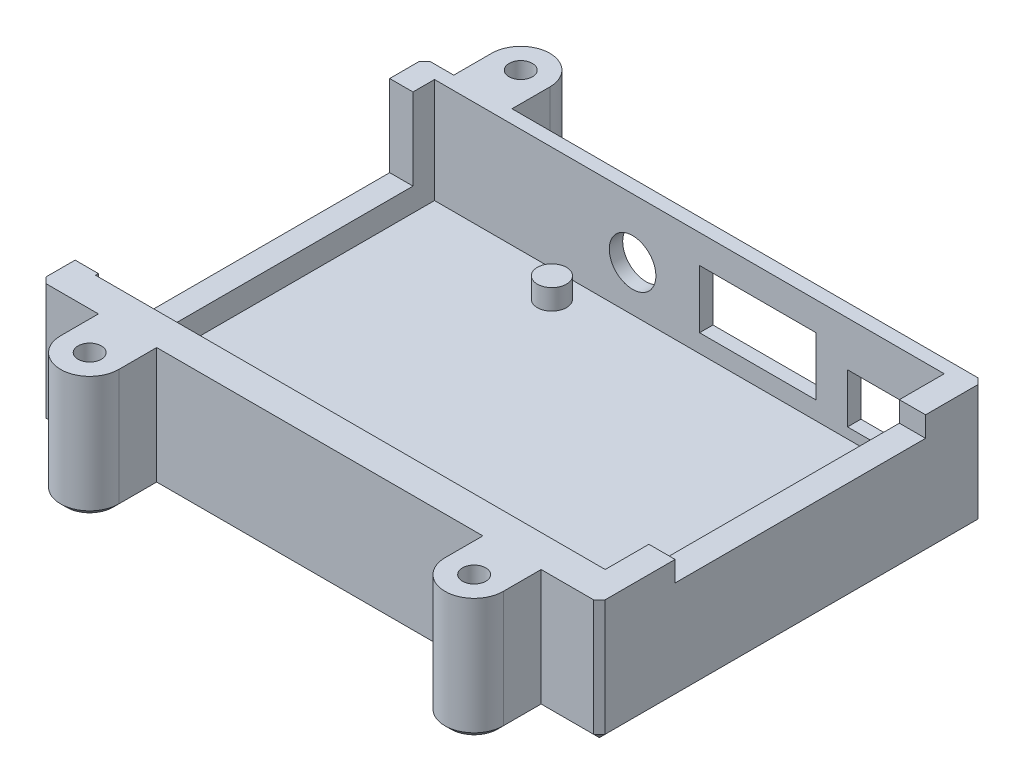
SolidWorks part; units mm, degrees
ref_plane "Front Plane" through (0, 0, 0) normal (0, 0, 1) x (1, 0, 0)
ref_plane "Top Plane" through (0, 0, 0) normal (0, 1, 0) x (1, 0, 0)
ref_plane "Right Plane" through (0, 0, 0) normal (1, 0, 0) x (0, 0, -1)
sketch "Sketch1" plane through (0, 0, 0) normal (0, 1, 0) x (1, 0, 0)
  line L0 (-33, -33) -> (-33, -39.5) construction
  line L1 (48, 33) -> (-48, 33)
  line L2 (48, 33) -> (48, -33)
  line L3 (48, -33) -> (-48, -33)
  line L4 (-48, 33) -> (-48, -33)
  line L5 (48, 33) -> (-48, -33) construction
  line L6 (48, -33) -> (-48, 33) construction
  line L7 (-28, -33) -> (-28, -39.5)
  line L8 (-38, -33) -> (-38, -39.5)
  line L9 (0, 18.5223) -> (0, -49.7489) construction
  line L10 (33, -33) -> (33, -39.5) construction
  line L11 (28, -33) -> (28, -39.5)
  line L12 (38, -33) -> (38, -39.5)
  line L13 (-38, 39.5) -> (-38, 33) construction
  line L14 (-33, 39.5) -> (-33, 33)
  line L15 (-43, 39.5) -> (-43, 33)
  arc A0 (-28, -33) -> (-38, -33) centre (-33, -33) ccw
  arc A1 (-38, -39.5) -> (-28, -39.5) centre (-33, -39.5) ccw
  arc A2 (28, -33) -> (38, -33) centre (33, -33) cw
  arc A3 (38, -39.5) -> (28, -39.5) centre (33, -39.5) cw
  arc A4 (-33, 39.5) -> (-43, 39.5) centre (-38, 39.5) ccw
  arc A5 (-43, 33) -> (-33, 33) centre (-38, 33) ccw
  circle A6 centre (-38, 39.5) radius 2
  circle A7 centre (-33, -39.5) radius 2
  circle A8 centre (33, -39.5) radius 2
  point P0 (0, 0)
  point P8 (-33, -36.25)
  point P17 (33, -36.25)
  point P24 (-38, 36.25)
  dimension "D3" = 5
  dimension "D6" = 5
  dimension "D9" = 4
  dimension "D1" = 66
  dimension "D2" = 96
  dimension "D4" = 15
  dimension "D5" = 6.5
  dimension "D7" = 6.5
  dimension "D8" = 10
extrude "Boss-Extrude2" add sketch "Sketch1" along normal blind 3 contours L4 L3 L2 L1
sketch "Sketch4" plane through (0, 0, 0) normal (0, 1, 0) x (1, 0, 0)
  line L0 (-38, 33) -> (-38, 39.5) construction
  line L1 (48, 33) -> (-48, 33) construction
  line L2 (-43, 33) -> (-43, 39.5)
  line L3 (-33, 33) -> (-33, 39.5)
  line L4 (-33, -33) -> (-33, -39.5) construction
  line L5 (48, -33) -> (-48, -33) construction
  line L6 (-28, -33) -> (-28, -39.5)
  line L7 (-38, -33) -> (-38, -39.5)
  line L8 (33, -33) -> (33, -39.5) construction
  line L9 (38, -33) -> (38, -39.5)
  line L10 (28, -33) -> (28, -39.5)
  line L11 (-48, 33) -> (-48, -33) construction
  line L12 (48, 33) -> (48, -33) construction
  arc A0 (-43, 33) -> (-33, 33) centre (-38, 33) ccw
  arc A1 (-33, 39.5) -> (-43, 39.5) centre (-38, 39.5) ccw
  arc A2 (-28, -33) -> (-38, -33) centre (-33, -33) ccw
  arc A3 (-38, -39.5) -> (-28, -39.5) centre (-33, -39.5) ccw
  arc A4 (38, -33) -> (28, -33) centre (33, -33) ccw
  arc A5 (28, -39.5) -> (38, -39.5) centre (33, -39.5) ccw
  circle A6 centre (-38, 39.5) radius 2
  circle A9 centre (-33, -39.5) radius 2
  circle A10 centre (33, -39.5) radius 2
  point P4 (-38, 36.25)
  point P9 (-33, -36.25)
  point P18 (33, -36.25)
  dimension "D2" = 5
  dimension "D4" = 15
  dimension "D6" = 4
  dimension "D1" = 6.5
  dimension "D3" = 10
  dimension "D5" = 15
extrude "Boss-Extrude3" add sketch "Sketch4" along normal blind 3
sketch "Sketch8" plane through (0, 3, 0) normal (0, 1, 0) x (1, 0, 0)
  line L0 (43.5, 30.7) -> (43.5, -27.5)
  line L1 (43.5, 30.7) -> (-44, 30.7)
  line L2 (48, 33) -> (48, -33) construction
  line L3 (48, 33) -> (-33, 33) construction
  line L4 (-44, 30.7) -> (-44, -27.5)
  line L5 (-48, 33) -> (-48, -33) construction
  line L6 (-44, -27.5) -> (43.5, -27.5)
  line L7 (28, -33) -> (-28, -33) construction
  line L8 (-0.25, 30.7) -> (-0.25, -27.5) construction
  line L9 (-44, 1.6) -> (43.5, 1.6) construction
  line L10 (38.75, 26.1) -> (38.75, -22.9) construction
  line L11 (42.25, 29.6) -> (-42.75, 29.6)
  line L12 (42.25, 29.6) -> (42.25, -26.4)
  line L13 (42.25, -26.4) -> (-42.75, -26.4)
  line L14 (-42.75, 29.6) -> (-42.75, -26.4)
  line L15 (42.25, 29.6) -> (-42.75, -26.4) construction
  line L16 (42.25, -26.4) -> (-42.75, 29.6) construction
  line L17 (-19.25, 26.1) -> (38.75, 26.1) construction
  line L18 (-48, 33) -> (-48, -33)
  line L19 (-48, -33) -> (48, -33)
  line L20 (48, -33) -> (48, 33)
  line L21 (48, 33) -> (-48, 33)
  circle A0 centre (38.75, 26.1) radius 2.5
  circle A1 centre (38.75, -22.9) radius 2.5
  circle A2 centre (-19.25, 26.1) radius 2.5
  circle A3 centre (-19.25, -22.9) radius 2.5
  point P16 (-0.25, 1.6)
  point P25 (38.75, 1.6)
  dimension "D7" = 5
  dimension "D8" = 49
  dimension "D10" = 49
  dimension "D1" = 4.5
  dimension "D2" = 2.3
  dimension "D3" = 4
  dimension "D4" = 5.5
  dimension "D5" = 85
  dimension "D6" = 56
  dimension "D9" = 58
  dimension "D11" = 3.5
  dimension "D12" = 3.5
extrude "Boss-Extrude5" add sketch "Sketch8" along normal blind 3.5 contours A2 | A0 | A1 | A3
sketch "Sketch9" plane through (0, 3, 0) normal (0, 1, 0) x (1, 0, 0)
  line L0 (-48, 33) -> (-48, -33) construction
  line L1 (-44, -27.5) -> (43.5, -27.5)
  line L2 (-44, -27.5) -> (-44, 30.7)
  line L3 (-44, 30.7) -> (43.5, 30.7)
  line L4 (43.5, -27.5) -> (43.5, 30.7)
  line L5 (48, 33) -> (-33, 33) construction
  line L6 (48, 33) -> (48, -33) construction
  line L7 (28, -33) -> (-28, -33) construction
  line L9 (-48, -33) -> (48, -33)
  line L10 (-48, -33) -> (-48, 33)
  line L11 (-48, 33) -> (48, 33)
  line L12 (48, -33) -> (48, 33)
  dimension "D1" = 4
  dimension "D2" = 2.3
  dimension "D3" = 4.5
  dimension "D4" = 5.5
extrude "Boss-Extrude6" add sketch "Sketch9" along normal blind 18
sketch "Sketch11" plane through (-48, 0, 0) normal (-1, 0, 0) x (0, 0, 1)
  line L0 (-33, 21) -> (33, 21) construction
  line L1 (-27, 21) -> (27, 21)
  line L2 (-27, 21) -> (-27, 7)
  line L3 (-27, 7) -> (27, 7)
  line L4 (27, 21) -> (27, 7)
  line L5 (-33, 21) -> (-33, 0) construction
  line L6 (33, 21) -> (33, 0) construction
  dimension "D1" = 14
  dimension "D2" = 54
  dimension "D3" = 6
  dimension "D4" = 6
extrude "Cut-Extrude1" cut sketch "Sketch11" against normal up to surface (4 mm away) up to face at (-44, 12, -1.6)
sketch "Sketch12" plane through (48, 0, 0) normal (1, 0, 0) x (0, 0, -1)
  line L0 (-33, 21) -> (33, 21) construction
  line L1 (-20, 21) -> (23, 21)
  line L2 (-20, 21) -> (-20, 17.5)
  line L3 (-20, 17.5) -> (23, 17.5)
  line L4 (23, 21) -> (23, 17.5)
  line L5 (-33, 21) -> (-33, 0) construction
  line L6 (33, 21) -> (33, 0) construction
  dimension "D1" = 3.5
  dimension "D2" = 13
  dimension "D3" = 10
extrude "Cut-Extrude2" cut sketch "Sketch12" against normal up to surface (4.5 mm away) up to face at (43.5, 12, -1.6)
sketch "Sketch13" plane through (43.5, 0, 0) normal (-1, 0, 0) x (0, 0, 1)
  line L0 (27.5, 3) -> (-30.7, 3) construction
  line L1 (-9.075, 3) -> (6.925, 3)
  line L2 (-9.075, 3) -> (-9.075, 8)
  line L3 (-9.075, 8) -> (6.925, 8)
  line L4 (6.925, 3) -> (6.925, 8)
  line L10 (-30.7, 21) -> (-30.7, 3) construction
  point P6 (-1.075, 8)
  dimension "D1" = 16
  dimension "D2" = 29.625
  dimension "D3" = 5
extrude "Cut-Extrude3" cut sketch "Sketch13" against normal blind 3.5
sketch "Sketch14" plane through (0, 0, -33) normal (0, 0, -1) x (-1, 0, 0)
  line L1 (-38.9, 4.8) -> (-26.9, 4.8)
  line L2 (-38.9, 4.8) -> (-38.9, 13.3)
  line L3 (-38.9, 13.3) -> (-26.9, 13.3)
  line L4 (-26.9, 4.8) -> (-26.9, 13.3)
  line L5 (-48, 0) -> (33, 0) construction
  line L6 (-48, 21) -> (-48, 0) construction
  line L7 (-21.5, 6.1) -> (-1.5, 6.1)
  line L8 (-21.5, 6.1) -> (-21.5, 16.1)
  line L9 (-21.5, 16.1) -> (-1.5, 16.1)
  line L10 (-1.5, 6.1) -> (-1.5, 16.1)
  circle A0 centre (10, 10.8) radius 4
  point P4 (-32.9, 13.3)
  point P13 (-11.5, 16.1)
  point P16 (-38.9, 9.05)
  point P17 (-21.5, 11.1)
  dimension "D9" = 8
  dimension "D1" = 8.5
  dimension "D2" = 12
  dimension "D3" = 15.1
  dimension "D4" = 9.05
  dimension "D5" = 10
  dimension "D6" = 20
  dimension "D7" = 11.1
  dimension "D8" = 36.5
  dimension "D10" = 58
  dimension "D11" = 10.8
extrude "Cut-Extrude4" cut sketch "Sketch14" against normal up to surface (2.3 mm away) up to face at (-0.25, 12, -30.7)
sketch "Sketch16" plane through (0, 3, 0) normal (0, 1, 0) x (1, 0, 0)
  line L0 (-43, 33) -> (-33, 33)
  line L1 (-33, 33) -> (-33, 39.5)
  line L2 (-43, 33) -> (-43, 39.5)
  line L3 (-38, -33) -> (-38, -39.5)
  line L4 (-38, -33) -> (-28, -33)
  line L5 (-28, -33) -> (-28, -39.5)
  line L6 (28, -39.5) -> (28, -33)
  line L7 (28, -33) -> (38, -33)
  line L8 (38, -39.5) -> (38, -33) construction
  line L9 (38, -33) -> (38, -39.5)
  arc A0 (-33, 39.5) -> (-43, 39.5) centre (-38, 39.5) ccw
  arc A1 (-33, 39.5) -> (-43, 39.5) centre (-38, 39.5) ccw construction
  circle A2 centre (-38, 39.5) radius 2
  arc A3 (-38, -39.5) -> (-28, -39.5) centre (-33, -39.5) ccw
  circle A4 centre (-33, -39.5) radius 2
  arc A5 (28, -39.5) -> (38, -39.5) centre (33, -39.5) ccw
  circle A6 centre (33, -39.5) radius 2
extrude "Boss-Extrude7" add sketch "Sketch16" along normal up to surface (18 mm away) up to face at (-0.125, 21, -28.425)
chamfer "Chamfer2" distance 1 angle 45 20 edges at (0, 0, 33) (43, 0, 33) (48, 10.5, 33) (48, 0, 0) (7.5, 0, -33) (48, 10.5, -33) (-45.5, 0, -33) (-43, 0, 33) (-48, 10.5, 33) (-48, 0, 0) (-48, 10.5, -33) (38, 0, 36.25) (33, 0, 44.5) (28, 0, 36.25) (-28, 0, 36.25) (-33, 0, 44.5) (-38, 0, 36.25) (-33, 0, -36.25) (-38, 0, -44.5) (-43, 0, -36.25)
